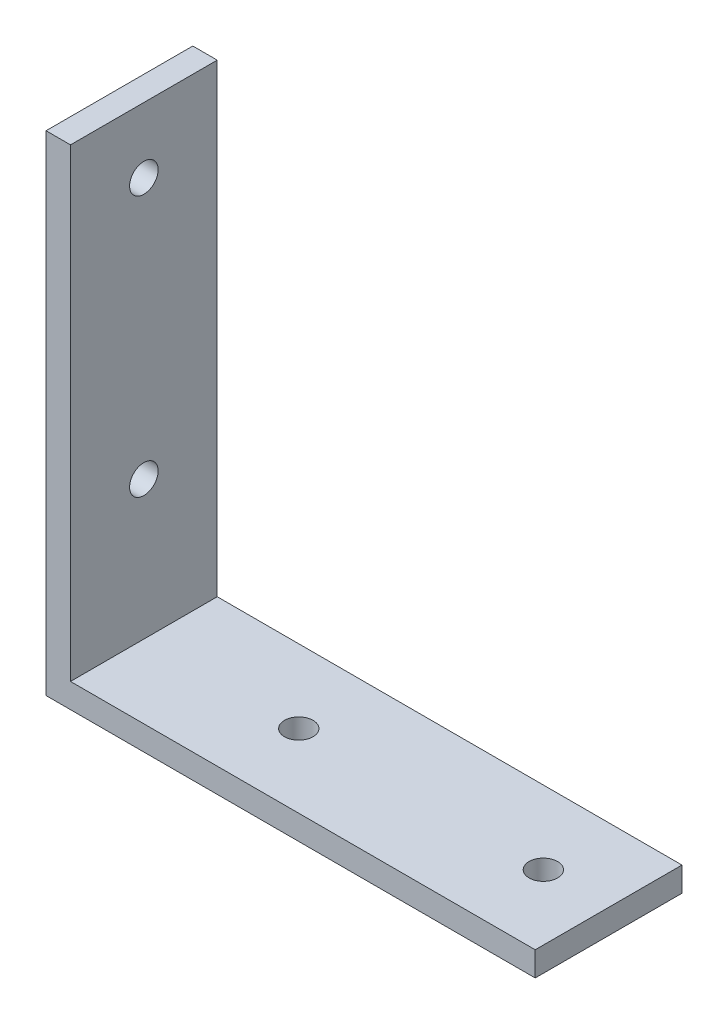
SolidWorks part; units mm, degrees
ref_plane "前视基准面" through (0, 0, 0) normal (0, 0, 1) x (1, 0, 0)
ref_plane "上视基准面" through (0, 0, 0) normal (0, 1, 0) x (1, 0, 0)
ref_plane "右视基准面" through (0, 0, 0) normal (1, 0, 0) x (0, 0, -1)
other "Configuration Table"
sketch "草图2" plane through (0, 0, 0) normal (0, 0, 1) x (1, 0, 0)
  line L0 (0, 0) -> (60, 0)
  line L1 (60, 0) -> (60, 3)
  line L2 (60, 3) -> (3, 3)
  line L3 (3, 3) -> (3, 60)
  line L4 (3, 60) -> (0, 60)
  line L5 (0, 60) -> (0, 0)
  dimension "D1" = 60
  dimension "D2" = 60
  dimension "D3" = 3
  dimension "D4" = 3
extrude "凸台-拉伸1" add sketch "草图2" along normal blind 18
ref_plane "基准面1" through (0, 13, 0) normal (0, 1, 0) x (1, 0, 0)
ref_plane "基准面2" through (13, 0, 0) normal (1, 0, 0) x (0, 0, -1)
sketch "草图3" plane through (13, 0, 0) normal (1, 0, 0) x (0, 0, -1)
  line L0 (-9, -940) -> (-9, 49060) construction
  line L1 (-18, 60) -> (0, 60) construction
  circle A0 centre (-9, 52) radius 1.75
  circle A2 centre (-9, 20) radius 1.75
  point P5 (-9, 60)
  dimension "D1" = 8
  dimension "D3" = 3.5
  dimension "D4" = 3.5
  dimension "D2" = 32
extrude "切除-拉伸1" cut sketch "草图3" against normal through all
sketch "草图4" plane through (0, 13, 0) normal (0, 1, 0) x (1, 0, 0)
  line L0 (124.8787, -9) -> (-4.8787, -9) construction
  circle A0 centre (52, -9) radius 1.75
  circle A1 centre (22, -9) radius 1.75
  point P3 (60, -9)
  dimension "D1" = 3.5
  dimension "D2" = 3.5
  dimension "D3" = 8
  dimension "D4" = 30
extrude "切除-拉伸3" cut sketch "草图4" against normal through all
